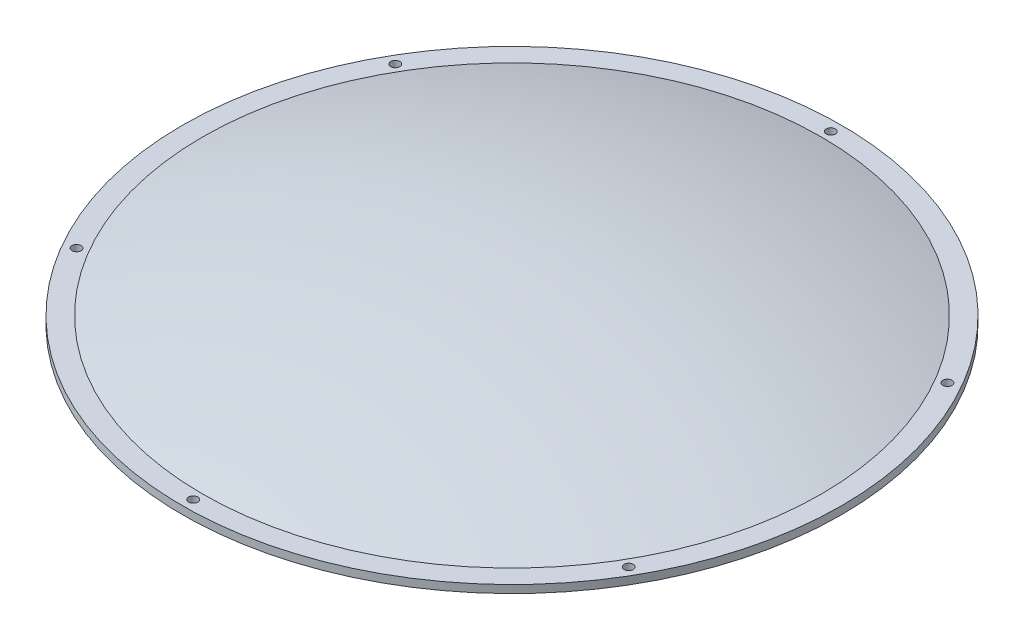
SolidWorks part; units mm, degrees
material "6061-T6 (SS)"
ref_plane "Front Plane" through (0, 0, 0) normal (0, 0, 1) x (1, 0, 0)
ref_plane "Top Plane" through (0, 0, 0) normal (0, 1, 0) x (1, 0, 0)
ref_plane "Right Plane" through (0, 0, 0) normal (1, 0, 0) x (0, 0, -1)
sketch "Sketch1" plane through (0, 0, 0) normal (0, 0, 1) x (1, 0, 0)
  line L0 (-107.3799, 282.8427) -> (107.3799, 282.8427)
  line L1 (0, 282.8427) -> (0, 102.1032)
  line L2 (0, 302.54) -> (0, 300)
  line L3 (100, 282.8427) -> (107, 282.8427)
  line L4 (0, 300) -> (-94.3927, 300) construction
  line L5 (100.4348, 285.3827) -> (107, 285.3827)
  line L6 (107, 282.8427) -> (107, 285.3827)
  line L7 (-100, 282.8427) -> (0, 0) construction
  line L8 (0, 0) -> (100, 282.8427) construction
  arc A0 (107.3799, 282.8427) -> (-107.3799, 282.8427) centre (0, 0) ccw
  arc A1 (100, 282.8427) -> (-100, 282.8427) centre (0, 0) ccw
  circle A2 centre (0, 0) radius 300 construction
  circle A3 centre (0, 0) radius 302.54 construction
  circle A4 centre (0, 0) radius 300 construction
  point P1 (149, 0)
  point P5 (0, 302.54)
  point P8 (143.4457, 43.8558)
  dimension "D1" = 300
  dimension "D2" = 200
  dimension "D4" = 2.54
  dimension "D5" = 107
  dimension "D3" = 2.54
revolve "Revolve1" add sketch "Sketch1" angle 360 about L1
sketch "Sketch4" plane through (0, 282.8427, 0) normal (0, -1, 0) x (1, 0, 0)
  circle A0 centre (0, 0) radius 103.5 construction
  circle A1 centre (0, 103.5) radius 1.4732
  circle A2 centre (89.6336, 51.75) radius 1.4732
  circle A3 centre (89.6336, -51.75) radius 1.4732
  circle A4 centre (0, -103.5) radius 1.4732
  circle A5 centre (-89.6336, -51.75) radius 1.4732
  circle A6 centre (-89.6336, 51.75) radius 1.4732
  dimension "D1" = 207
  dimension "D2" = 2.9464
  dimension "D3" = 6
extrude "Cut-Extrude1" cut sketch "Sketch4" against normal through all
ref_plane "Plane1" through (0, 152, 0) normal (0, 1, 0) x (-1, 0, 0)
sketch "Sketch5" plane through (0, 152, 0) normal (0, 1, 0) x (-1, 0, 0)
  line L0 (0.866, 0) -> (2.4628, 0) construction
  line L1 (0.433, -0.75) -> (0.866, 0)
  line L2 (0.866, 0) -> (0.433, 0.75)
  line L3 (0.433, 0.75) -> (-0.433, 0.75)
  line L4 (-0.433, 0.75) -> (-0.866, 0)
  line L5 (-0.866, 0) -> (-0.433, -0.75)
  line L6 (-0.433, -0.75) -> (0.433, -0.75)
  line L7 (2.557, -0.75) -> (3.423, -0.75)
  line L8 (2.363, 0.8643) -> (1.93, 1.6143)
  line L9 (1.93, 1.6143) -> (1.064, 1.6143)
  line L10 (1.064, 1.6143) -> (0.631, 0.8643)
  line L11 (0.631, 0.8643) -> (1.064, 0.1143)
  line L12 (1.064, 0.1143) -> (1.93, 0.1143)
  line L13 (1.93, 0.1143) -> (2.363, 0.8643)
  line L14 (2.124, 0) -> (2.557, -0.75)
  line L15 (2.557, 0.75) -> (2.124, 0)
  line L16 (3.423, 0.75) -> (2.557, 0.75)
  line L17 (3.856, 0) -> (3.423, 0.75)
  line L18 (3.423, -0.75) -> (3.856, 0)
  line L19 (3.621, 0.8643) -> (4.054, 0.1143)
  line L20 (4.054, 1.6143) -> (3.621, 0.8643)
  line L21 (4.92, 1.6143) -> (4.054, 1.6143)
  line L22 (5.353, 0.8643) -> (4.92, 1.6143)
  line L23 (4.92, 0.1143) -> (5.353, 0.8643)
  line L24 (4.054, 0.1143) -> (4.92, 0.1143)
  line L25 (5.547, -0.75) -> (6.413, -0.75)
  line L26 (5.114, 0) -> (5.547, -0.75)
  line L27 (5.547, 0.75) -> (5.114, 0)
  line L28 (6.413, 0.75) -> (5.547, 0.75)
  line L29 (6.846, 0) -> (6.413, 0.75)
  line L30 (6.413, -0.75) -> (6.846, 0)
  line L31 (6.611, 0.8643) -> (7.044, 0.1143)
  line L32 (7.044, 1.6143) -> (6.611, 0.8643)
  line L33 (7.91, 1.6143) -> (7.044, 1.6143)
  line L34 (8.343, 0.8643) -> (7.91, 1.6143)
  line L35 (7.91, 0.1143) -> (8.343, 0.8643)
  line L36 (7.044, 0.1143) -> (7.91, 0.1143)
  line L37 (8.537, -0.75) -> (9.403, -0.75)
  line L38 (8.104, 0) -> (8.537, -0.75)
  line L39 (8.537, 0.75) -> (8.104, 0)
  line L40 (9.403, 0.75) -> (8.537, 0.75)
  line L41 (9.836, 0) -> (9.403, 0.75)
  line L42 (9.403, -0.75) -> (9.836, 0)
  line L43 (9.601, 0.8643) -> (10.034, 0.1143)
  line L44 (10.034, 1.6143) -> (9.601, 0.8643)
  line L45 (10.9, 1.6143) -> (10.034, 1.6143)
  line L46 (11.333, 0.8643) -> (10.9, 1.6143)
  line L47 (10.9, 0.1143) -> (11.333, 0.8643)
  line L48 (10.034, 0.1143) -> (10.9, 0.1143)
  line L49 (11.527, -0.75) -> (12.393, -0.75)
  line L50 (11.094, 0) -> (11.527, -0.75)
  line L51 (11.527, 0.75) -> (11.094, 0)
  line L52 (12.393, 0.75) -> (11.527, 0.75)
  line L53 (12.826, 0) -> (12.393, 0.75)
  line L54 (12.393, -0.75) -> (12.826, 0)
  line L55 (12.591, 0.8643) -> (13.024, 0.1143)
  line L56 (13.024, 1.6143) -> (12.591, 0.8643)
  line L57 (13.89, 1.6143) -> (13.024, 1.6143)
  line L58 (14.323, 0.8643) -> (13.89, 1.6143)
  line L59 (13.89, 0.1143) -> (14.323, 0.8643)
  line L60 (13.024, 0.1143) -> (13.89, 0.1143)
  line L61 (14.517, -0.75) -> (15.383, -0.75)
  line L62 (14.084, 0) -> (14.517, -0.75)
  line L63 (14.517, 0.75) -> (14.084, 0)
  line L64 (15.383, 0.75) -> (14.517, 0.75)
  line L65 (15.816, 0) -> (15.383, 0.75)
  line L66 (15.383, -0.75) -> (15.816, 0)
  line L67 (15.581, 0.8643) -> (16.014, 0.1143)
  line L68 (16.014, 1.6143) -> (15.581, 0.8643)
  line L69 (16.88, 1.6143) -> (16.014, 1.6143)
  line L70 (17.313, 0.8643) -> (16.88, 1.6143)
  line L71 (16.88, 0.1143) -> (17.313, 0.8643)
  line L72 (16.014, 0.1143) -> (16.88, 0.1143)
  line L73 (17.507, -0.75) -> (18.373, -0.75)
  line L74 (17.074, 0) -> (17.507, -0.75)
  line L75 (17.507, 0.75) -> (17.074, 0)
  line L76 (18.373, 0.75) -> (17.507, 0.75)
  line L77 (18.806, 0) -> (18.373, 0.75)
  line L78 (18.373, -0.75) -> (18.806, 0)
  line L79 (18.571, 0.8643) -> (19.004, 0.1143)
  line L80 (19.004, 1.6143) -> (18.571, 0.8643)
  line L81 (19.87, 1.6143) -> (19.004, 1.6143)
  line L82 (20.303, 0.8643) -> (19.87, 1.6143)
  line L83 (19.87, 0.1143) -> (20.303, 0.8643)
  line L84 (19.004, 0.1143) -> (19.87, 0.1143)
  line L85 (20.497, -0.75) -> (21.363, -0.75)
  line L86 (20.064, 0) -> (20.497, -0.75)
  line L87 (20.497, 0.75) -> (20.064, 0)
  line L88 (21.363, 0.75) -> (20.497, 0.75)
  line L89 (21.796, 0) -> (21.363, 0.75)
  line L90 (21.363, -0.75) -> (21.796, 0)
  line L91 (21.561, 0.8643) -> (21.994, 0.1143)
  line L92 (21.994, 1.6143) -> (21.561, 0.8643)
  line L93 (22.86, 1.6143) -> (21.994, 1.6143)
  line L94 (23.293, 0.8643) -> (22.86, 1.6143)
  line L95 (22.86, 0.1143) -> (23.293, 0.8643)
  line L96 (21.994, 0.1143) -> (22.86, 0.1143)
  line L97 (23.487, -0.75) -> (24.353, -0.75)
  line L98 (23.054, 0) -> (23.487, -0.75)
  line L99 (23.487, 0.75) -> (23.054, 0)
  line L100 (24.353, 0.75) -> (23.487, 0.75)
  line L101 (24.786, 0) -> (24.353, 0.75)
  line L102 (24.353, -0.75) -> (24.786, 0)
  line L103 (24.551, 0.8643) -> (24.984, 0.1143)
  line L104 (24.984, 1.6143) -> (24.551, 0.8643)
  line L105 (25.85, 1.6143) -> (24.984, 1.6143)
  line L106 (26.283, 0.8643) -> (25.85, 1.6143)
  line L107 (25.85, 0.1143) -> (26.283, 0.8643)
  line L108 (24.984, 0.1143) -> (25.85, 0.1143)
  line L109 (26.477, -0.75) -> (27.343, -0.75)
  line L110 (26.044, 0) -> (26.477, -0.75)
  line L111 (26.477, 0.75) -> (26.044, 0)
  line L112 (27.343, 0.75) -> (26.477, 0.75)
  line L113 (27.776, 0) -> (27.343, 0.75)
  line L114 (27.343, -0.75) -> (27.776, 0)
  line L115 (27.541, 0.8643) -> (27.974, 0.1143)
  line L116 (27.974, 1.6143) -> (27.541, 0.8643)
  line L117 (28.84, 1.6143) -> (27.974, 1.6143)
  line L118 (29.273, 0.8643) -> (28.84, 1.6143)
  line L119 (28.84, 0.1143) -> (29.273, 0.8643)
  line L120 (27.974, 0.1143) -> (28.84, 0.1143)
  line L121 (-0.433, 0.98) -> (0.433, 0.98)
  line L122 (-0.866, 1.73) -> (-0.433, 0.98)
  line L123 (-0.433, 2.48) -> (-0.866, 1.73)
  line L124 (0.433, 2.48) -> (-0.433, 2.48)
  line L125 (0.866, 1.73) -> (0.433, 2.48)
  line L126 (0.433, 0.98) -> (0.866, 1.73)
  line L127 (0.631, 2.5943) -> (1.064, 1.8443)
  line L128 (1.064, 3.3443) -> (0.631, 2.5943)
  line L129 (1.93, 3.3443) -> (1.064, 3.3443)
  line L130 (2.363, 2.5943) -> (1.93, 3.3443)
  line L131 (1.93, 1.8443) -> (2.363, 2.5943)
  line L132 (1.064, 1.8443) -> (1.93, 1.8443)
  line L133 (2.557, 0.98) -> (3.423, 0.98)
  line L134 (2.124, 1.73) -> (2.557, 0.98)
  line L135 (2.557, 2.48) -> (2.124, 1.73)
  line L136 (3.423, 2.48) -> (2.557, 2.48)
  line L137 (3.856, 1.73) -> (3.423, 2.48)
  line L138 (3.423, 0.98) -> (3.856, 1.73)
  line L139 (3.621, 2.5943) -> (4.054, 1.8443)
  line L140 (4.054, 3.3443) -> (3.621, 2.5943)
  line L141 (4.92, 3.3443) -> (4.054, 3.3443)
  line L142 (5.353, 2.5943) -> (4.92, 3.3443)
  line L143 (4.92, 1.8443) -> (5.353, 2.5943)
  line L144 (4.054, 1.8443) -> (4.92, 1.8443)
  line L145 (5.547, 0.98) -> (6.413, 0.98)
  line L146 (5.114, 1.73) -> (5.547, 0.98)
  line L147 (5.547, 2.48) -> (5.114, 1.73)
  line L148 (6.413, 2.48) -> (5.547, 2.48)
  line L149 (6.846, 1.73) -> (6.413, 2.48)
  line L150 (6.413, 0.98) -> (6.846, 1.73)
  line L151 (6.611, 2.5943) -> (7.044, 1.8443)
  line L152 (7.044, 3.3443) -> (6.611, 2.5943)
  line L153 (7.91, 3.3443) -> (7.044, 3.3443)
  line L154 (8.343, 2.5943) -> (7.91, 3.3443)
  line L155 (7.91, 1.8443) -> (8.343, 2.5943)
  line L156 (7.044, 1.8443) -> (7.91, 1.8443)
  line L157 (8.537, 0.98) -> (9.403, 0.98)
  line L158 (8.104, 1.73) -> (8.537, 0.98)
  line L159 (8.537, 2.48) -> (8.104, 1.73)
  line L160 (9.403, 2.48) -> (8.537, 2.48)
  line L161 (9.836, 1.73) -> (9.403, 2.48)
  line L162 (9.403, 0.98) -> (9.836, 1.73)
  line L163 (9.601, 2.5943) -> (10.034, 1.8443)
  line L164 (10.034, 3.3443) -> (9.601, 2.5943)
  line L165 (10.9, 3.3443) -> (10.034, 3.3443)
  line L166 (11.333, 2.5943) -> (10.9, 3.3443)
  line L167 (10.9, 1.8443) -> (11.333, 2.5943)
  line L168 (10.034, 1.8443) -> (10.9, 1.8443)
  line L169 (11.527, 0.98) -> (12.393, 0.98)
  line L170 (11.094, 1.73) -> (11.527, 0.98)
  line L171 (11.527, 2.48) -> (11.094, 1.73)
  line L172 (12.393, 2.48) -> (11.527, 2.48)
  line L173 (12.826, 1.73) -> (12.393, 2.48)
  line L174 (12.393, 0.98) -> (12.826, 1.73)
  line L175 (12.591, 2.5943) -> (13.024, 1.8443)
  line L176 (13.024, 3.3443) -> (12.591, 2.5943)
  line L177 (13.89, 3.3443) -> (13.024, 3.3443)
  line L178 (14.323, 2.5943) -> (13.89, 3.3443)
  line L179 (13.89, 1.8443) -> (14.323, 2.5943)
  line L180 (13.024, 1.8443) -> (13.89, 1.8443)
  line L181 (14.517, 0.98) -> (15.383, 0.98)
  line L182 (14.084, 1.73) -> (14.517, 0.98)
  line L183 (14.517, 2.48) -> (14.084, 1.73)
  line L184 (15.383, 2.48) -> (14.517, 2.48)
  line L185 (15.816, 1.73) -> (15.383, 2.48)
  line L186 (15.383, 0.98) -> (15.816, 1.73)
  line L187 (15.581, 2.5943) -> (16.014, 1.8443)
  line L188 (16.014, 3.3443) -> (15.581, 2.5943)
  line L189 (16.88, 3.3443) -> (16.014, 3.3443)
  line L190 (17.313, 2.5943) -> (16.88, 3.3443)
  line L191 (16.88, 1.8443) -> (17.313, 2.5943)
  line L192 (16.014, 1.8443) -> (16.88, 1.8443)
  line L193 (17.507, 0.98) -> (18.373, 0.98)
  line L194 (17.074, 1.73) -> (17.507, 0.98)
  line L195 (17.507, 2.48) -> (17.074, 1.73)
  line L196 (18.373, 2.48) -> (17.507, 2.48)
  line L197 (18.806, 1.73) -> (18.373, 2.48)
  line L198 (18.373, 0.98) -> (18.806, 1.73)
  line L199 (18.571, 2.5943) -> (19.004, 1.8443)
  line L200 (19.004, 3.3443) -> (18.571, 2.5943)
  line L201 (19.87, 3.3443) -> (19.004, 3.3443)
  line L202 (20.303, 2.5943) -> (19.87, 3.3443)
  line L203 (19.87, 1.8443) -> (20.303, 2.5943)
  line L204 (19.004, 1.8443) -> (19.87, 1.8443)
  line L205 (20.497, 0.98) -> (21.363, 0.98)
  line L206 (20.064, 1.73) -> (20.497, 0.98)
  line L207 (20.497, 2.48) -> (20.064, 1.73)
  line L208 (21.363, 2.48) -> (20.497, 2.48)
  line L209 (21.796, 1.73) -> (21.363, 2.48)
  line L210 (21.363, 0.98) -> (21.796, 1.73)
  line L211 (21.561, 2.5943) -> (21.994, 1.8443)
  line L212 (21.994, 3.3443) -> (21.561, 2.5943)
  line L213 (22.86, 3.3443) -> (21.994, 3.3443)
  line L214 (23.293, 2.5943) -> (22.86, 3.3443)
  line L215 (22.86, 1.8443) -> (23.293, 2.5943)
  line L216 (21.994, 1.8443) -> (22.86, 1.8443)
  line L217 (23.487, 0.98) -> (24.353, 0.98)
  line L218 (23.054, 1.73) -> (23.487, 0.98)
  line L219 (23.487, 2.48) -> (23.054, 1.73)
  line L220 (24.353, 2.48) -> (23.487, 2.48)
  line L221 (24.786, 1.73) -> (24.353, 2.48)
  line L222 (24.353, 0.98) -> (24.786, 1.73)
  line L223 (24.551, 2.5943) -> (24.984, 1.8443)
  line L224 (24.984, 3.3443) -> (24.551, 2.5943)
  line L225 (25.85, 3.3443) -> (24.984, 3.3443)
  line L226 (26.283, 2.5943) -> (25.85, 3.3443)
  line L227 (25.85, 1.8443) -> (26.283, 2.5943)
  line L228 (24.984, 1.8443) -> (25.85, 1.8443)
  line L229 (26.477, 0.98) -> (27.343, 0.98)
  line L230 (26.044, 1.73) -> (26.477, 0.98)
  line L231 (26.477, 2.48) -> (26.044, 1.73)
  line L232 (27.343, 2.48) -> (26.477, 2.48)
  line L233 (27.776, 1.73) -> (27.343, 2.48)
  line L234 (27.343, 0.98) -> (27.776, 1.73)
  line L235 (27.541, 2.5943) -> (27.974, 1.8443)
  line L236 (27.974, 3.3443) -> (27.541, 2.5943)
  line L237 (28.84, 3.3443) -> (27.974, 3.3443)
  line L238 (29.273, 2.5943) -> (28.84, 3.3443)
  line L239 (28.84, 1.8443) -> (29.273, 2.5943)
  line L240 (27.974, 1.8443) -> (28.84, 1.8443)
  line L241 (-0.433, 2.71) -> (0.433, 2.71)
  line L242 (-0.866, 3.46) -> (-0.433, 2.71)
  line L243 (-0.433, 4.21) -> (-0.866, 3.46)
  line L244 (0.433, 4.21) -> (-0.433, 4.21)
  line L245 (0.866, 3.46) -> (0.433, 4.21)
  line L246 (0.433, 2.71) -> (0.866, 3.46)
  line L247 (0.631, 4.3243) -> (1.064, 3.5743)
  line L248 (1.064, 5.0743) -> (0.631, 4.3243)
  line L249 (1.93, 5.0743) -> (1.064, 5.0743)
  line L250 (2.363, 4.3243) -> (1.93, 5.0743)
  line L251 (1.93, 3.5743) -> (2.363, 4.3243)
  line L252 (1.064, 3.5743) -> (1.93, 3.5743)
  line L253 (2.557, 2.71) -> (3.423, 2.71)
  line L254 (2.124, 3.46) -> (2.557, 2.71)
  line L255 (2.557, 4.21) -> (2.124, 3.46)
  line L256 (3.423, 4.21) -> (2.557, 4.21)
  line L257 (3.856, 3.46) -> (3.423, 4.21)
  line L258 (3.423, 2.71) -> (3.856, 3.46)
  line L259 (3.621, 4.3243) -> (4.054, 3.5743)
  line L260 (4.054, 5.0743) -> (3.621, 4.3243)
  line L261 (4.92, 5.0743) -> (4.054, 5.0743)
  line L262 (5.353, 4.3243) -> (4.92, 5.0743)
  line L263 (4.92, 3.5743) -> (5.353, 4.3243)
  line L264 (4.054, 3.5743) -> (4.92, 3.5743)
  line L265 (5.547, 2.71) -> (6.413, 2.71)
  line L266 (5.114, 3.46) -> (5.547, 2.71)
  line L267 (5.547, 4.21) -> (5.114, 3.46)
  line L268 (6.413, 4.21) -> (5.547, 4.21)
  line L269 (6.846, 3.46) -> (6.413, 4.21)
  line L270 (6.413, 2.71) -> (6.846, 3.46)
  line L271 (6.611, 4.3243) -> (7.044, 3.5743)
  line L272 (7.044, 5.0743) -> (6.611, 4.3243)
  line L273 (7.91, 5.0743) -> (7.044, 5.0743)
  line L274 (8.343, 4.3243) -> (7.91, 5.0743)
  line L275 (7.91, 3.5743) -> (8.343, 4.3243)
  line L276 (7.044, 3.5743) -> (7.91, 3.5743)
  line L277 (8.537, 2.71) -> (9.403, 2.71)
  line L278 (8.104, 3.46) -> (8.537, 2.71)
  line L279 (8.537, 4.21) -> (8.104, 3.46)
  line L280 (9.403, 4.21) -> (8.537, 4.21)
  line L281 (9.836, 3.46) -> (9.403, 4.21)
  line L282 (9.403, 2.71) -> (9.836, 3.46)
  line L283 (9.601, 4.3243) -> (10.034, 3.5743)
  line L284 (10.034, 5.0743) -> (9.601, 4.3243)
  line L285 (10.9, 5.0743) -> (10.034, 5.0743)
  line L286 (11.333, 4.3243) -> (10.9, 5.0743)
  line L287 (10.9, 3.5743) -> (11.333, 4.3243)
  line L288 (10.034, 3.5743) -> (10.9, 3.5743)
  line L289 (11.527, 2.71) -> (12.393, 2.71)
  line L290 (11.094, 3.46) -> (11.527, 2.71)
  line L291 (11.527, 4.21) -> (11.094, 3.46)
  line L292 (12.393, 4.21) -> (11.527, 4.21)
  line L293 (12.826, 3.46) -> (12.393, 4.21)
  line L294 (12.393, 2.71) -> (12.826, 3.46)
  line L295 (12.591, 4.3243) -> (13.024, 3.5743)
  line L296 (13.024, 5.0743) -> (12.591, 4.3243)
  line L297 (13.89, 5.0743) -> (13.024, 5.0743)
  line L298 (14.323, 4.3243) -> (13.89, 5.0743)
  line L299 (13.89, 3.5743) -> (14.323, 4.3243)
  line L300 (13.024, 3.5743) -> (13.89, 3.5743)
  line L301 (14.517, 2.71) -> (15.383, 2.71)
  line L302 (14.084, 3.46) -> (14.517, 2.71)
  line L303 (14.517, 4.21) -> (14.084, 3.46)
  line L304 (15.383, 4.21) -> (14.517, 4.21)
  line L305 (15.816, 3.46) -> (15.383, 4.21)
  line L306 (15.383, 2.71) -> (15.816, 3.46)
  line L307 (15.581, 4.3243) -> (16.014, 3.5743)
  line L308 (16.014, 5.0743) -> (15.581, 4.3243)
  line L309 (16.88, 5.0743) -> (16.014, 5.0743)
  line L310 (17.313, 4.3243) -> (16.88, 5.0743)
  line L311 (16.88, 3.5743) -> (17.313, 4.3243)
  line L312 (16.014, 3.5743) -> (16.88, 3.5743)
  line L313 (17.507, 2.71) -> (18.373, 2.71)
  line L314 (17.074, 3.46) -> (17.507, 2.71)
  line L315 (17.507, 4.21) -> (17.074, 3.46)
  line L316 (18.373, 4.21) -> (17.507, 4.21)
  line L317 (18.806, 3.46) -> (18.373, 4.21)
  line L318 (18.373, 2.71) -> (18.806, 3.46)
  line L319 (18.571, 4.3243) -> (19.004, 3.5743)
  line L320 (19.004, 5.0743) -> (18.571, 4.3243)
  line L321 (19.87, 5.0743) -> (19.004, 5.0743)
  line L322 (20.303, 4.3243) -> (19.87, 5.0743)
  line L323 (19.87, 3.5743) -> (20.303, 4.3243)
  line L324 (19.004, 3.5743) -> (19.87, 3.5743)
  line L325 (20.497, 2.71) -> (21.363, 2.71)
  line L326 (20.064, 3.46) -> (20.497, 2.71)
  line L327 (20.497, 4.21) -> (20.064, 3.46)
  line L328 (21.363, 4.21) -> (20.497, 4.21)
  line L329 (21.796, 3.46) -> (21.363, 4.21)
  line L330 (21.363, 2.71) -> (21.796, 3.46)
  line L331 (21.561, 4.3243) -> (21.994, 3.5743)
  line L332 (21.994, 5.0743) -> (21.561, 4.3243)
  line L333 (22.86, 5.0743) -> (21.994, 5.0743)
  line L334 (23.293, 4.3243) -> (22.86, 5.0743)
  line L335 (22.86, 3.5743) -> (23.293, 4.3243)
  line L336 (21.994, 3.5743) -> (22.86, 3.5743)
  line L337 (23.487, 2.71) -> (24.353, 2.71)
  line L338 (23.054, 3.46) -> (23.487, 2.71)
  line L339 (23.487, 4.21) -> (23.054, 3.46)
  line L340 (24.353, 4.21) -> (23.487, 4.21)
  line L341 (24.786, 3.46) -> (24.353, 4.21)
  line L342 (24.353, 2.71) -> (24.786, 3.46)
  line L343 (24.551, 4.3243) -> (24.984, 3.5743)
  line L344 (24.984, 5.0743) -> (24.551, 4.3243)
  line L345 (25.85, 5.0743) -> (24.984, 5.0743)
  line L346 (26.283, 4.3243) -> (25.85, 5.0743)
  line L347 (25.85, 3.5743) -> (26.283, 4.3243)
  line L348 (24.984, 3.5743) -> (25.85, 3.5743)
  line L349 (26.477, 2.71) -> (27.343, 2.71)
  line L350 (26.044, 3.46) -> (26.477, 2.71)
  line L351 (26.477, 4.21) -> (26.044, 3.46)
  line L352 (27.343, 4.21) -> (26.477, 4.21)
  line L353 (27.776, 3.46) -> (27.343, 4.21)
  line L354 (27.343, 2.71) -> (27.776, 3.46)
  line L355 (27.541, 4.3243) -> (27.974, 3.5743)
  line L356 (27.974, 5.0743) -> (27.541, 4.3243)
  line L357 (28.84, 5.0743) -> (27.974, 5.0743)
  line L358 (29.273, 4.3243) -> (28.84, 5.0743)
  line L359 (28.84, 3.5743) -> (29.273, 4.3243)
  line L360 (27.974, 3.5743) -> (28.84, 3.5743)
  line L361 (-0.433, 4.44) -> (0.433, 4.44)
  line L362 (-0.866, 5.19) -> (-0.433, 4.44)
  line L363 (-0.433, 5.94) -> (-0.866, 5.19)
  line L364 (0.433, 5.94) -> (-0.433, 5.94)
  line L365 (0.866, 5.19) -> (0.433, 5.94)
  line L366 (0.433, 4.44) -> (0.866, 5.19)
  line L367 (0.631, 6.0543) -> (1.064, 5.3043)
  line L368 (1.064, 6.8043) -> (0.631, 6.0543)
  line L369 (1.93, 6.8043) -> (1.064, 6.8043)
  line L370 (2.363, 6.0543) -> (1.93, 6.8043)
  line L371 (1.93, 5.3043) -> (2.363, 6.0543)
  line L372 (1.064, 5.3043) -> (1.93, 5.3043)
  line L373 (2.557, 4.44) -> (3.423, 4.44)
  line L374 (2.124, 5.19) -> (2.557, 4.44)
  line L375 (2.557, 5.94) -> (2.124, 5.19)
  line L376 (3.423, 5.94) -> (2.557, 5.94)
  line L377 (3.856, 5.19) -> (3.423, 5.94)
  line L378 (3.423, 4.44) -> (3.856, 5.19)
  line L379 (3.621, 6.0543) -> (4.054, 5.3043)
  line L380 (4.054, 6.8043) -> (3.621, 6.0543)
  line L381 (4.92, 6.8043) -> (4.054, 6.8043)
  line L382 (5.353, 6.0543) -> (4.92, 6.8043)
  line L383 (4.92, 5.3043) -> (5.353, 6.0543)
  line L384 (4.054, 5.3043) -> (4.92, 5.3043)
  line L385 (5.547, 4.44) -> (6.413, 4.44)
  line L386 (5.114, 5.19) -> (5.547, 4.44)
  line L387 (5.547, 5.94) -> (5.114, 5.19)
  line L388 (6.413, 5.94) -> (5.547, 5.94)
  line L389 (6.846, 5.19) -> (6.413, 5.94)
  line L390 (6.413, 4.44) -> (6.846, 5.19)
  line L391 (6.611, 6.0543) -> (7.044, 5.3043)
  line L392 (7.044, 6.8043) -> (6.611, 6.0543)
  line L393 (7.91, 6.8043) -> (7.044, 6.8043)
  line L394 (8.343, 6.0543) -> (7.91, 6.8043)
  line L395 (7.91, 5.3043) -> (8.343, 6.0543)
  line L396 (7.044, 5.3043) -> (7.91, 5.3043)
  line L397 (8.537, 4.44) -> (9.403, 4.44)
  line L398 (8.104, 5.19) -> (8.537, 4.44)
  line L399 (8.537, 5.94) -> (8.104, 5.19)
  line L400 (9.403, 5.94) -> (8.537, 5.94)
  line L401 (9.836, 5.19) -> (9.403, 5.94)
  line L402 (9.403, 4.44) -> (9.836, 5.19)
  line L403 (9.601, 6.0543) -> (10.034, 5.3043)
  line L404 (10.034, 6.8043) -> (9.601, 6.0543)
  line L405 (10.9, 6.8043) -> (10.034, 6.8043)
  line L406 (11.333, 6.0543) -> (10.9, 6.8043)
  line L407 (10.9, 5.3043) -> (11.333, 6.0543)
  line L408 (10.034, 5.3043) -> (10.9, 5.3043)
  line L409 (11.527, 4.44) -> (12.393, 4.44)
  line L410 (11.094, 5.19) -> (11.527, 4.44)
  line L411 (11.527, 5.94) -> (11.094, 5.19)
  line L412 (12.393, 5.94) -> (11.527, 5.94)
  line L413 (12.826, 5.19) -> (12.393, 5.94)
  line L414 (12.393, 4.44) -> (12.826, 5.19)
  line L415 (12.591, 6.0543) -> (13.024, 5.3043)
  line L416 (13.024, 6.8043) -> (12.591, 6.0543)
  line L417 (13.89, 6.8043) -> (13.024, 6.8043)
  line L418 (14.323, 6.0543) -> (13.89, 6.8043)
  line L419 (13.89, 5.3043) -> (14.323, 6.0543)
  line L420 (13.024, 5.3043) -> (13.89, 5.3043)
  line L421 (14.517, 4.44) -> (15.383, 4.44)
  line L422 (14.084, 5.19) -> (14.517, 4.44)
  line L423 (14.517, 5.94) -> (14.084, 5.19)
  line L424 (15.383, 5.94) -> (14.517, 5.94)
  line L425 (15.816, 5.19) -> (15.383, 5.94)
  line L426 (15.383, 4.44) -> (15.816, 5.19)
  line L427 (15.581, 6.0543) -> (16.014, 5.3043)
  line L428 (16.014, 6.8043) -> (15.581, 6.0543)
  line L429 (16.88, 6.8043) -> (16.014, 6.8043)
  line L430 (17.313, 6.0543) -> (16.88, 6.8043)
  line L431 (16.88, 5.3043) -> (17.313, 6.0543)
  line L432 (16.014, 5.3043) -> (16.88, 5.3043)
  line L433 (17.507, 4.44) -> (18.373, 4.44)
  line L434 (17.074, 5.19) -> (17.507, 4.44)
  line L435 (17.507, 5.94) -> (17.074, 5.19)
  line L436 (18.373, 5.94) -> (17.507, 5.94)
  line L437 (18.806, 5.19) -> (18.373, 5.94)
  line L438 (18.373, 4.44) -> (18.806, 5.19)
  line L439 (18.571, 6.0543) -> (19.004, 5.3043)
  line L440 (19.004, 6.8043) -> (18.571, 6.0543)
  line L441 (19.87, 6.8043) -> (19.004, 6.8043)
  line L442 (20.303, 6.0543) -> (19.87, 6.8043)
  line L443 (19.87, 5.3043) -> (20.303, 6.0543)
  line L444 (19.004, 5.3043) -> (19.87, 5.3043)
  line L445 (20.497, 4.44) -> (21.363, 4.44)
  line L446 (20.064, 5.19) -> (20.497, 4.44)
  line L447 (20.497, 5.94) -> (20.064, 5.19)
  line L448 (21.363, 5.94) -> (20.497, 5.94)
  line L449 (21.796, 5.19) -> (21.363, 5.94)
  line L450 (21.363, 4.44) -> (21.796, 5.19)
  line L451 (21.561, 6.0543) -> (21.994, 5.3043)
  line L452 (21.994, 6.8043) -> (21.561, 6.0543)
  line L453 (22.86, 6.8043) -> (21.994, 6.8043)
  line L454 (23.293, 6.0543) -> (22.86, 6.8043)
  line L455 (22.86, 5.3043) -> (23.293, 6.0543)
  line L456 (21.994, 5.3043) -> (22.86, 5.3043)
  line L457 (23.487, 4.44) -> (24.353, 4.44)
  line L458 (23.054, 5.19) -> (23.487, 4.44)
  line L459 (23.487, 5.94) -> (23.054, 5.19)
  line L460 (24.353, 5.94) -> (23.487, 5.94)
  line L461 (24.786, 5.19) -> (24.353, 5.94)
  line L462 (24.353, 4.44) -> (24.786, 5.19)
  line L463 (24.551, 6.0543) -> (24.984, 5.3043)
  line L464 (24.984, 6.8043) -> (24.551, 6.0543)
  line L465 (25.85, 6.8043) -> (24.984, 6.8043)
  line L466 (26.283, 6.0543) -> (25.85, 6.8043)
  line L467 (25.85, 5.3043) -> (26.283, 6.0543)
  line L468 (24.984, 5.3043) -> (25.85, 5.3043)
  line L469 (26.477, 4.44) -> (27.343, 4.44)
  line L470 (26.044, 5.19) -> (26.477, 4.44)
  line L471 (26.477, 5.94) -> (26.044, 5.19)
  line L472 (27.343, 5.94) -> (26.477, 5.94)
  line L473 (27.776, 5.19) -> (27.343, 5.94)
  line L474 (27.343, 4.44) -> (27.776, 5.19)
  line L475 (27.541, 6.0543) -> (27.974, 5.3043)
  line L476 (27.974, 6.8043) -> (27.541, 6.0543)
  line L477 (28.84, 6.8043) -> (27.974, 6.8043)
  line L478 (29.273, 6.0543) -> (28.84, 6.8043)
  line L479 (28.84, 5.3043) -> (29.273, 6.0543)
  line L480 (27.974, 5.3043) -> (28.84, 5.3043)
  line L481 (-0.433, 6.17) -> (0.433, 6.17)
  line L482 (-0.866, 6.92) -> (-0.433, 6.17)
  line L483 (-0.433, 7.67) -> (-0.866, 6.92)
  line L484 (0.433, 7.67) -> (-0.433, 7.67)
  line L485 (0.866, 6.92) -> (0.433, 7.67)
  line L486 (0.433, 6.17) -> (0.866, 6.92)
  line L487 (0.631, 7.7843) -> (1.064, 7.0343)
  line L488 (1.064, 8.5343) -> (0.631, 7.7843)
  line L489 (1.93, 8.5343) -> (1.064, 8.5343)
  line L490 (2.363, 7.7843) -> (1.93, 8.5343)
  line L491 (1.93, 7.0343) -> (2.363, 7.7843)
  line L492 (1.064, 7.0343) -> (1.93, 7.0343)
  line L493 (2.557, 6.17) -> (3.423, 6.17)
  line L494 (2.124, 6.92) -> (2.557, 6.17)
  line L495 (2.557, 7.67) -> (2.124, 6.92)
  line L496 (3.423, 7.67) -> (2.557, 7.67)
  line L497 (3.856, 6.92) -> (3.423, 7.67)
  line L498 (3.423, 6.17) -> (3.856, 6.92)
  line L499 (3.621, 7.7843) -> (4.054, 7.0343)
  line L500 (4.054, 8.5343) -> (3.621, 7.7843)
  line L501 (4.92, 8.5343) -> (4.054, 8.5343)
  line L502 (5.353, 7.7843) -> (4.92, 8.5343)
  line L503 (4.92, 7.0343) -> (5.353, 7.7843)
  line L504 (4.054, 7.0343) -> (4.92, 7.0343)
  line L505 (5.547, 6.17) -> (6.413, 6.17)
  line L506 (5.114, 6.92) -> (5.547, 6.17)
  line L507 (5.547, 7.67) -> (5.114, 6.92)
  line L508 (6.413, 7.67) -> (5.547, 7.67)
  line L509 (6.846, 6.92) -> (6.413, 7.67)
  line L510 (6.413, 6.17) -> (6.846, 6.92)
  line L511 (6.611, 7.7843) -> (7.044, 7.0343)
  line L512 (7.044, 8.5343) -> (6.611, 7.7843)
  line L513 (7.91, 8.5343) -> (7.044, 8.5343)
  line L514 (8.343, 7.7843) -> (7.91, 8.5343)
  line L515 (7.91, 7.0343) -> (8.343, 7.7843)
  line L516 (7.044, 7.0343) -> (7.91, 7.0343)
  line L517 (8.537, 6.17) -> (9.403, 6.17)
  line L518 (8.104, 6.92) -> (8.537, 6.17)
  line L519 (8.537, 7.67) -> (8.104, 6.92)
  line L520 (9.403, 7.67) -> (8.537, 7.67)
  line L521 (9.836, 6.92) -> (9.403, 7.67)
  line L522 (9.403, 6.17) -> (9.836, 6.92)
  line L523 (9.601, 7.7843) -> (10.034, 7.0343)
  line L524 (10.034, 8.5343) -> (9.601, 7.7843)
  line L525 (10.9, 8.5343) -> (10.034, 8.5343)
  line L526 (11.333, 7.7843) -> (10.9, 8.5343)
  line L527 (10.9, 7.0343) -> (11.333, 7.7843)
  line L528 (10.034, 7.0343) -> (10.9, 7.0343)
  line L529 (11.527, 6.17) -> (12.393, 6.17)
  line L530 (11.094, 6.92) -> (11.527, 6.17)
  line L531 (11.527, 7.67) -> (11.094, 6.92)
  line L532 (12.393, 7.67) -> (11.527, 7.67)
  line L533 (12.826, 6.92) -> (12.393, 7.67)
  line L534 (12.393, 6.17) -> (12.826, 6.92)
  line L535 (12.591, 7.7843) -> (13.024, 7.0343)
  line L536 (13.024, 8.5343) -> (12.591, 7.7843)
  line L537 (13.89, 8.5343) -> (13.024, 8.5343)
  line L538 (14.323, 7.7843) -> (13.89, 8.5343)
  line L539 (13.89, 7.0343) -> (14.323, 7.7843)
  line L540 (13.024, 7.0343) -> (13.89, 7.0343)
  line L541 (14.517, 6.17) -> (15.383, 6.17)
  line L542 (14.084, 6.92) -> (14.517, 6.17)
  line L543 (14.517, 7.67) -> (14.084, 6.92)
  line L544 (15.383, 7.67) -> (14.517, 7.67)
  line L545 (15.816, 6.92) -> (15.383, 7.67)
  line L546 (15.383, 6.17) -> (15.816, 6.92)
  line L547 (15.581, 7.7843) -> (16.014, 7.0343)
  line L548 (16.014, 8.5343) -> (15.581, 7.7843)
  line L549 (16.88, 8.5343) -> (16.014, 8.5343)
  line L550 (17.313, 7.7843) -> (16.88, 8.5343)
  line L551 (16.88, 7.0343) -> (17.313, 7.7843)
  line L552 (16.014, 7.0343) -> (16.88, 7.0343)
  line L553 (17.507, 6.17) -> (18.373, 6.17)
  line L554 (17.074, 6.92) -> (17.507, 6.17)
  line L555 (17.507, 7.67) -> (17.074, 6.92)
  line L556 (18.373, 7.67) -> (17.507, 7.67)
  line L557 (18.806, 6.92) -> (18.373, 7.67)
  line L558 (18.373, 6.17) -> (18.806, 6.92)
  line L559 (18.571, 7.7843) -> (19.004, 7.0343)
  line L560 (19.004, 8.5343) -> (18.571, 7.7843)
  line L561 (19.87, 8.5343) -> (19.004, 8.5343)
  line L562 (20.303, 7.7843) -> (19.87, 8.5343)
  line L563 (19.87, 7.0343) -> (20.303, 7.7843)
  line L564 (19.004, 7.0343) -> (19.87, 7.0343)
  line L565 (20.497, 6.17) -> (21.363, 6.17)
  line L566 (20.064, 6.92) -> (20.497, 6.17)
  line L567 (20.497, 7.67) -> (20.064, 6.92)
  line L568 (21.363, 7.67) -> (20.497, 7.67)
  line L569 (21.796, 6.92) -> (21.363, 7.67)
  line L570 (21.363, 6.17) -> (21.796, 6.92)
  line L571 (21.561, 7.7843) -> (21.994, 7.0343)
  line L572 (21.994, 8.5343) -> (21.561, 7.7843)
  line L573 (22.86, 8.5343) -> (21.994, 8.5343)
  line L574 (23.293, 7.7843) -> (22.86, 8.5343)
  line L575 (22.86, 7.0343) -> (23.293, 7.7843)
  line L576 (21.994, 7.0343) -> (22.86, 7.0343)
  line L577 (23.487, 6.17) -> (24.353, 6.17)
  line L578 (23.054, 6.92) -> (23.487, 6.17)
  line L579 (23.487, 7.67) -> (23.054, 6.92)
  line L580 (24.353, 7.67) -> (23.487, 7.67)
  line L581 (24.786, 6.92) -> (24.353, 7.67)
  line L582 (24.353, 6.17) -> (24.786, 6.92)
  line L583 (24.551, 7.7843) -> (24.984, 7.0343)
  line L584 (24.984, 8.5343) -> (24.551, 7.7843)
  line L585 (25.85, 8.5343) -> (24.984, 8.5343)
  line L586 (26.283, 7.7843) -> (25.85, 8.5343)
  line L587 (25.85, 7.0343) -> (26.283, 7.7843)
  line L588 (24.984, 7.0343) -> (25.85, 7.0343)
  line L589 (26.477, 6.17) -> (27.343, 6.17)
  line L590 (26.044, 6.92) -> (26.477, 6.17)
  line L591 (26.477, 7.67) -> (26.044, 6.92)
  line L592 (27.343, 7.67) -> (26.477, 7.67)
  line L593 (27.776, 6.92) -> (27.343, 7.67)
  line L594 (27.343, 6.17) -> (27.776, 6.92)
  line L595 (27.541, 7.7843) -> (27.974, 7.0343)
  line L596 (27.974, 8.5343) -> (27.541, 7.7843)
  line L597 (28.84, 8.5343) -> (27.974, 8.5343)
  line L598 (29.273, 7.7843) -> (28.84, 8.5343)
  line L599 (28.84, 7.0343) -> (29.273, 7.7843)
  line L600 (27.974, 7.0343) -> (28.84, 7.0343)
  line L601 (-0.433, 7.9) -> (0.433, 7.9)
  line L602 (-0.866, 8.65) -> (-0.433, 7.9)
  line L603 (-0.433, 9.4) -> (-0.866, 8.65)
  line L604 (0.433, 9.4) -> (-0.433, 9.4)
  line L605 (0.866, 8.65) -> (0.433, 9.4)
  line L606 (0.433, 7.9) -> (0.866, 8.65)
  line L607 (0.631, 9.5143) -> (1.064, 8.7643)
  line L608 (1.064, 10.2643) -> (0.631, 9.5143)
  line L609 (1.93, 10.2643) -> (1.064, 10.2643)
  line L610 (2.363, 9.5143) -> (1.93, 10.2643)
  line L611 (1.93, 8.7643) -> (2.363, 9.5143)
  line L612 (1.064, 8.7643) -> (1.93, 8.7643)
  line L613 (2.557, 7.9) -> (3.423, 7.9)
  line L614 (2.124, 8.65) -> (2.557, 7.9)
  line L615 (2.557, 9.4) -> (2.124, 8.65)
  line L616 (3.423, 9.4) -> (2.557, 9.4)
  line L617 (3.856, 8.65) -> (3.423, 9.4)
  line L618 (3.423, 7.9) -> (3.856, 8.65)
  line L619 (3.621, 9.5143) -> (4.054, 8.7643)
  line L620 (4.054, 10.2643) -> (3.621, 9.5143)
  line L621 (4.92, 10.2643) -> (4.054, 10.2643)
  line L622 (5.353, 9.5143) -> (4.92, 10.2643)
  line L623 (4.92, 8.7643) -> (5.353, 9.5143)
  line L624 (4.054, 8.7643) -> (4.92, 8.7643)
  line L625 (5.547, 7.9) -> (6.413, 7.9)
  line L626 (5.114, 8.65) -> (5.547, 7.9)
  line L627 (5.547, 9.4) -> (5.114, 8.65)
  line L628 (6.413, 9.4) -> (5.547, 9.4)
  line L629 (6.846, 8.65) -> (6.413, 9.4)
  line L630 (6.413, 7.9) -> (6.846, 8.65)
  line L631 (6.611, 9.5143) -> (7.044, 8.7643)
  line L632 (7.044, 10.2643) -> (6.611, 9.5143)
  line L633 (7.91, 10.2643) -> (7.044, 10.2643)
  line L634 (8.343, 9.5143) -> (7.91, 10.2643)
  line L635 (7.91, 8.7643) -> (8.343, 9.5143)
  line L636 (7.044, 8.7643) -> (7.91, 8.7643)
  line L637 (8.537, 7.9) -> (9.403, 7.9)
  line L638 (8.104, 8.65) -> (8.537, 7.9)
  line L639 (8.537, 9.4) -> (8.104, 8.65)
  line L640 (9.403, 9.4) -> (8.537, 9.4)
  line L641 (9.836, 8.65) -> (9.403, 9.4)
  line L642 (9.403, 7.9) -> (9.836, 8.65)
  line L643 (9.601, 9.5143) -> (10.034, 8.7643)
  line L644 (10.034, 10.2643) -> (9.601, 9.5143)
  line L645 (10.9, 10.2643) -> (10.034, 10.2643)
  line L646 (11.333, 9.5143) -> (10.9, 10.2643)
  line L647 (10.9, 8.7643) -> (11.333, 9.5143)
  line L648 (10.034, 8.7643) -> (10.9, 8.7643)
  line L649 (11.527, 7.9) -> (12.393, 7.9)
  line L650 (11.094, 8.65) -> (11.527, 7.9)
  line L651 (11.527, 9.4) -> (11.094, 8.65)
  line L652 (12.393, 9.4) -> (11.527, 9.4)
  line L653 (12.826, 8.65) -> (12.393, 9.4)
  line L654 (12.393, 7.9) -> (12.826, 8.65)
  line L655 (12.591, 9.5143) -> (13.024, 8.7643)
  line L656 (13.024, 10.2643) -> (12.591, 9.5143)
  line L657 (13.89, 10.2643) -> (13.024, 10.2643)
  line L658 (14.323, 9.5143) -> (13.89, 10.2643)
  line L659 (13.89, 8.7643) -> (14.323, 9.5143)
  line L660 (13.024, 8.7643) -> (13.89, 8.7643)
  line L661 (14.517, 7.9) -> (15.383, 7.9)
  line L662 (14.084, 8.65) -> (14.517, 7.9)
  line L663 (14.517, 9.4) -> (14.084, 8.65)
  line L664 (15.383, 9.4) -> (14.517, 9.4)
  line L665 (15.816, 8.65) -> (15.383, 9.4)
  line L666 (15.383, 7.9) -> (15.816, 8.65)
  line L667 (15.581, 9.5143) -> (16.014, 8.7643)
  line L668 (16.014, 10.2643) -> (15.581, 9.5143)
  line L669 (16.88, 10.2643) -> (16.014, 10.2643)
  line L670 (17.313, 9.5143) -> (16.88, 10.2643)
  line L671 (16.88, 8.7643) -> (17.313, 9.5143)
  line L672 (16.014, 8.7643) -> (16.88, 8.7643)
  line L673 (17.507, 7.9) -> (18.373, 7.9)
  line L674 (17.074, 8.65) -> (17.507, 7.9)
  line L675 (17.507, 9.4) -> (17.074, 8.65)
  line L676 (18.373, 9.4) -> (17.507, 9.4)
  line L677 (18.806, 8.65) -> (18.373, 9.4)
  line L678 (18.373, 7.9) -> (18.806, 8.65)
  line L679 (18.571, 9.5143) -> (19.004, 8.7643)
  line L680 (19.004, 10.2643) -> (18.571, 9.5143)
  line L681 (19.87, 10.2643) -> (19.004, 10.2643)
  line L682 (20.303, 9.5143) -> (19.87, 10.2643)
  line L683 (19.87, 8.7643) -> (20.303, 9.5143)
  line L684 (19.004, 8.7643) -> (19.87, 8.7643)
  line L685 (20.497, 7.9) -> (21.363, 7.9)
  line L686 (20.064, 8.65) -> (20.497, 7.9)
  line L687 (20.497, 9.4) -> (20.064, 8.65)
  line L688 (21.363, 9.4) -> (20.497, 9.4)
  line L689 (21.796, 8.65) -> (21.363, 9.4)
  line L690 (21.363, 7.9) -> (21.796, 8.65)
  line L691 (21.561, 9.5143) -> (21.994, 8.7643)
  line L692 (21.994, 10.2643) -> (21.561, 9.5143)
  line L693 (22.86, 10.2643) -> (21.994, 10.2643)
  line L694 (23.293, 9.5143) -> (22.86, 10.2643)
  line L695 (22.86, 8.7643) -> (23.293, 9.5143)
  line L696 (21.994, 8.7643) -> (22.86, 8.7643)
  line L697 (23.487, 7.9) -> (24.353, 7.9)
  line L698 (23.054, 8.65) -> (23.487, 7.9)
  line L699 (23.487, 9.4) -> (23.054, 8.65)
  line L700 (24.353, 9.4) -> (23.487, 9.4)
  line L701 (24.786, 8.65) -> (24.353, 9.4)
  line L702 (24.353, 7.9) -> (24.786, 8.65)
  line L703 (24.551, 9.5143) -> (24.984, 8.7643)
  line L704 (24.984, 10.2643) -> (24.551, 9.5143)
  line L705 (25.85, 10.2643) -> (24.984, 10.2643)
  line L706 (26.283, 9.5143) -> (25.85, 10.2643)
  line L707 (25.85, 8.7643) -> (26.283, 9.5143)
  line L708 (24.984, 8.7643) -> (25.85, 8.7643)
  line L709 (26.477, 7.9) -> (27.343, 7.9)
  line L710 (26.044, 8.65) -> (26.477, 7.9)
  line L711 (26.477, 9.4) -> (26.044, 8.65)
  line L712 (27.343, 9.4) -> (26.477, 9.4)
  line L713 (27.776, 8.65) -> (27.343, 9.4)
  line L714 (27.343, 7.9) -> (27.776, 8.65)
  line L715 (27.541, 9.5143) -> (27.974, 8.7643)
  line L716 (27.974, 10.2643) -> (27.541, 9.5143)
  line L717 (28.84, 10.2643) -> (27.974, 10.2643)
  line L718 (29.273, 9.5143) -> (28.84, 10.2643)
  line L719 (28.84, 8.7643) -> (29.273, 9.5143)
  line L720 (27.974, 8.7643) -> (28.84, 8.7643)
  line L721 (-0.433, 9.63) -> (0.433, 9.63)
  line L722 (-0.866, 10.38) -> (-0.433, 9.63)
  line L723 (-0.433, 11.13) -> (-0.866, 10.38)
  line L724 (0.433, 11.13) -> (-0.433, 11.13)
  line L725 (0.866, 10.38) -> (0.433, 11.13)
  line L726 (0.433, 9.63) -> (0.866, 10.38)
  line L727 (0.631, 11.2443) -> (1.064, 10.4943)
  line L728 (1.064, 11.9943) -> (0.631, 11.2443)
  line L729 (1.93, 11.9943) -> (1.064, 11.9943)
  line L730 (2.363, 11.2443) -> (1.93, 11.9943)
  line L731 (1.93, 10.4943) -> (2.363, 11.2443)
  line L732 (1.064, 10.4943) -> (1.93, 10.4943)
  line L733 (2.557, 9.63) -> (3.423, 9.63)
  line L734 (2.124, 10.38) -> (2.557, 9.63)
  line L735 (2.557, 11.13) -> (2.124, 10.38)
  line L736 (3.423, 11.13) -> (2.557, 11.13)
  line L737 (3.856, 10.38) -> (3.423, 11.13)
  line L738 (3.423, 9.63) -> (3.856, 10.38)
  line L739 (3.621, 11.2443) -> (4.054, 10.4943)
  line L740 (4.054, 11.9943) -> (3.621, 11.2443)
  line L741 (4.92, 11.9943) -> (4.054, 11.9943)
  line L742 (5.353, 11.2443) -> (4.92, 11.9943)
  line L743 (4.92, 10.4943) -> (5.353, 11.2443)
  line L744 (4.054, 10.4943) -> (4.92, 10.4943)
  line L745 (5.547, 9.63) -> (6.413, 9.63)
  line L746 (5.114, 10.38) -> (5.547, 9.63)
  line L747 (5.547, 11.13) -> (5.114, 10.38)
  line L748 (6.413, 11.13) -> (5.547, 11.13)
  line L749 (6.846, 10.38) -> (6.413, 11.13)
  line L750 (6.413, 9.63) -> (6.846, 10.38)
  line L751 (6.611, 11.2443) -> (7.044, 10.4943)
  line L752 (7.044, 11.9943) -> (6.611, 11.2443)
  line L753 (7.91, 11.9943) -> (7.044, 11.9943)
  line L754 (8.343, 11.2443) -> (7.91, 11.9943)
  line L755 (7.91, 10.4943) -> (8.343, 11.2443)
  line L756 (7.044, 10.4943) -> (7.91, 10.4943)
  line L757 (8.537, 9.63) -> (9.403, 9.63)
  line L758 (8.104, 10.38) -> (8.537, 9.63)
  line L759 (8.537, 11.13) -> (8.104, 10.38)
  line L760 (9.403, 11.13) -> (8.537, 11.13)
  line L761 (9.836, 10.38) -> (9.403, 11.13)
  line L762 (9.403, 9.63) -> (9.836, 10.38)
  line L763 (9.601, 11.2443) -> (10.034, 10.4943)
  line L764 (10.034, 11.9943) -> (9.601, 11.2443)
  line L765 (10.9, 11.9943) -> (10.034, 11.9943)
  line L766 (11.333, 11.2443) -> (10.9, 11.9943)
  line L767 (10.9, 10.4943) -> (11.333, 11.2443)
  line L768 (10.034, 10.4943) -> (10.9, 10.4943)
  line L769 (11.527, 9.63) -> (12.393, 9.63)
  line L770 (11.094, 10.38) -> (11.527, 9.63)
  line L771 (11.527, 11.13) -> (11.094, 10.38)
  line L772 (12.393, 11.13) -> (11.527, 11.13)
  line L773 (12.826, 10.38) -> (12.393, 11.13)
  line L774 (12.393, 9.63) -> (12.826, 10.38)
  line L775 (12.591, 11.2443) -> (13.024, 10.4943)
  line L776 (13.024, 11.9943) -> (12.591, 11.2443)
  line L777 (13.89, 11.9943) -> (13.024, 11.9943)
  line L778 (14.323, 11.2443) -> (13.89, 11.9943)
  line L779 (13.89, 10.4943) -> (14.323, 11.2443)
  line L780 (13.024, 10.4943) -> (13.89, 10.4943)
  line L781 (14.517, 9.63) -> (15.383, 9.63)
  line L782 (14.084, 10.38) -> (14.517, 9.63)
  line L783 (14.517, 11.13) -> (14.084, 10.38)
  line L784 (15.383, 11.13) -> (14.517, 11.13)
  line L785 (15.816, 10.38) -> (15.383, 11.13)
  line L786 (15.383, 9.63) -> (15.816, 10.38)
  line L787 (15.581, 11.2443) -> (16.014, 10.4943)
  line L788 (16.014, 11.9943) -> (15.581, 11.2443)
  line L789 (16.88, 11.9943) -> (16.014, 11.9943)
  line L790 (17.313, 11.2443) -> (16.88, 11.9943)
  line L791 (16.88, 10.4943) -> (17.313, 11.2443)
  line L792 (16.014, 10.4943) -> (16.88, 10.4943)
  line L793 (17.507, 9.63) -> (18.373, 9.63)
  line L794 (17.074, 10.38) -> (17.507, 9.63)
  line L795 (17.507, 11.13) -> (17.074, 10.38)
  line L796 (18.373, 11.13) -> (17.507, 11.13)
  line L797 (18.806, 10.38) -> (18.373, 11.13)
  line L798 (18.373, 9.63) -> (18.806, 10.38)
  line L799 (18.571, 11.2443) -> (19.004, 10.4943)
  line L800 (19.004, 11.9943) -> (18.571, 11.2443)
  line L801 (19.87, 11.9943) -> (19.004, 11.9943)
  line L802 (20.303, 11.2443) -> (19.87, 11.9943)
  line L803 (19.87, 10.4943) -> (20.303, 11.2443)
  line L804 (19.004, 10.4943) -> (19.87, 10.4943)
  line L805 (20.497, 9.63) -> (21.363, 9.63)
  line L806 (20.064, 10.38) -> (20.497, 9.63)
  line L807 (20.497, 11.13) -> (20.064, 10.38)
  line L808 (21.363, 11.13) -> (20.497, 11.13)
  line L809 (21.796, 10.38) -> (21.363, 11.13)
  line L810 (21.363, 9.63) -> (21.796, 10.38)
  line L811 (21.561, 11.2443) -> (21.994, 10.4943)
  line L812 (21.994, 11.9943) -> (21.561, 11.2443)
  line L813 (22.86, 11.9943) -> (21.994, 11.9943)
  line L814 (23.293, 11.2443) -> (22.86, 11.9943)
  line L815 (22.86, 10.4943) -> (23.293, 11.2443)
  line L816 (21.994, 10.4943) -> (22.86, 10.4943)
  line L817 (23.487, 9.63) -> (24.353, 9.63)
  line L818 (23.054, 10.38) -> (23.487, 9.63)
  line L819 (23.487, 11.13) -> (23.054, 10.38)
  line L820 (24.353, 11.13) -> (23.487, 11.13)
  line L821 (24.786, 10.38) -> (24.353, 11.13)
  line L822 (24.353, 9.63) -> (24.786, 10.38)
  line L823 (24.551, 11.2443) -> (24.984, 10.4943)
  line L824 (24.984, 11.9943) -> (24.551, 11.2443)
  line L825 (25.85, 11.9943) -> (24.984, 11.9943)
  line L826 (26.283, 11.2443) -> (25.85, 11.9943)
  line L827 (25.85, 10.4943) -> (26.283, 11.2443)
  line L828 (24.984, 10.4943) -> (25.85, 10.4943)
  line L829 (26.477, 9.63) -> (27.343, 9.63)
  line L830 (26.044, 10.38) -> (26.477, 9.63)
  line L831 (26.477, 11.13) -> (26.044, 10.38)
  line L832 (27.343, 11.13) -> (26.477, 11.13)
  line L833 (27.776, 10.38) -> (27.343, 11.13)
  line L834 (27.343, 9.63) -> (27.776, 10.38)
  line L835 (27.541, 11.2443) -> (27.974, 10.4943)
  line L836 (27.974, 11.9943) -> (27.541, 11.2443)
  line L837 (28.84, 11.9943) -> (27.974, 11.9943)
  line L838 (29.273, 11.2443) -> (28.84, 11.9943)
  line L839 (28.84, 10.4943) -> (29.273, 11.2443)
  line L840 (27.974, 10.4943) -> (28.84, 10.4943)
  line L841 (-0.433, 11.36) -> (0.433, 11.36)
  line L842 (-0.866, 12.11) -> (-0.433, 11.36)
  line L843 (-0.433, 12.86) -> (-0.866, 12.11)
  line L844 (0.433, 12.86) -> (-0.433, 12.86)
  line L845 (0.866, 12.11) -> (0.433, 12.86)
  line L846 (0.433, 11.36) -> (0.866, 12.11)
  line L847 (0.631, 12.9743) -> (1.064, 12.2243)
  line L848 (1.064, 13.7243) -> (0.631, 12.9743)
  line L849 (1.93, 13.7243) -> (1.064, 13.7243)
  line L850 (2.363, 12.9743) -> (1.93, 13.7243)
  line L851 (1.93, 12.2243) -> (2.363, 12.9743)
  line L852 (1.064, 12.2243) -> (1.93, 12.2243)
  line L853 (2.557, 11.36) -> (3.423, 11.36)
  line L854 (2.124, 12.11) -> (2.557, 11.36)
  line L855 (2.557, 12.86) -> (2.124, 12.11)
  line L856 (3.423, 12.86) -> (2.557, 12.86)
  line L857 (3.856, 12.11) -> (3.423, 12.86)
  line L858 (3.423, 11.36) -> (3.856, 12.11)
  line L859 (3.621, 12.9743) -> (4.054, 12.2243)
  line L860 (4.054, 13.7243) -> (3.621, 12.9743)
  line L861 (4.92, 13.7243) -> (4.054, 13.7243)
  line L862 (5.353, 12.9743) -> (4.92, 13.7243)
  line L863 (4.92, 12.2243) -> (5.353, 12.9743)
  line L864 (4.054, 12.2243) -> (4.92, 12.2243)
  line L865 (5.547, 11.36) -> (6.413, 11.36)
  line L866 (5.114, 12.11) -> (5.547, 11.36)
  line L867 (5.547, 12.86) -> (5.114, 12.11)
  line L868 (6.413, 12.86) -> (5.547, 12.86)
  line L869 (6.846, 12.11) -> (6.413, 12.86)
  line L870 (6.413, 11.36) -> (6.846, 12.11)
  line L871 (6.611, 12.9743) -> (7.044, 12.2243)
  line L872 (7.044, 13.7243) -> (6.611, 12.9743)
  line L873 (7.91, 13.7243) -> (7.044, 13.7243)
  line L874 (8.343, 12.9743) -> (7.91, 13.7243)
  line L875 (7.91, 12.2243) -> (8.343, 12.9743)
  line L876 (7.044, 12.2243) -> (7.91, 12.2243)
  line L877 (8.537, 11.36) -> (9.403, 11.36)
  line L878 (8.104, 12.11) -> (8.537, 11.36)
  line L879 (8.537, 12.86) -> (8.104, 12.11)
  line L880 (9.403, 12.86) -> (8.537, 12.86)
  line L881 (9.836, 12.11) -> (9.403, 12.86)
  line L882 (9.403, 11.36) -> (9.836, 12.11)
  line L883 (9.601, 12.9743) -> (10.034, 12.2243)
  line L884 (10.034, 13.7243) -> (9.601, 12.9743)
  line L885 (10.9, 13.7243) -> (10.034, 13.7243)
  line L886 (11.333, 12.9743) -> (10.9, 13.7243)
  line L887 (10.9, 12.2243) -> (11.333, 12.9743)
  line L888 (10.034, 12.2243) -> (10.9, 12.2243)
  line L889 (11.527, 11.36) -> (12.393, 11.36)
  line L890 (11.094, 12.11) -> (11.527, 11.36)
  line L891 (11.527, 12.86) -> (11.094, 12.11)
  line L892 (12.393, 12.86) -> (11.527, 12.86)
  line L893 (12.826, 12.11) -> (12.393, 12.86)
  line L894 (12.393, 11.36) -> (12.826, 12.11)
  line L895 (12.591, 12.9743) -> (13.024, 12.2243)
  line L896 (13.024, 13.7243) -> (12.591, 12.9743)
  line L897 (13.89, 13.7243) -> (13.024, 13.7243)
  line L898 (14.323, 12.9743) -> (13.89, 13.7243)
  line L899 (13.89, 12.2243) -> (14.323, 12.9743)
  line L900 (13.024, 12.2243) -> (13.89, 12.2243)
  line L901 (14.517, 11.36) -> (15.383, 11.36)
  line L902 (14.084, 12.11) -> (14.517, 11.36)
  line L903 (14.517, 12.86) -> (14.084, 12.11)
  line L904 (15.383, 12.86) -> (14.517, 12.86)
  line L905 (15.816, 12.11) -> (15.383, 12.86)
  line L906 (15.383, 11.36) -> (15.816, 12.11)
  line L907 (15.581, 12.9743) -> (16.014, 12.2243)
  line L908 (16.014, 13.7243) -> (15.581, 12.9743)
  line L909 (16.88, 13.7243) -> (16.014, 13.7243)
  line L910 (17.313, 12.9743) -> (16.88, 13.7243)
  line L911 (16.88, 12.2243) -> (17.313, 12.9743)
  line L912 (16.014, 12.2243) -> (16.88, 12.2243)
  line L913 (17.507, 11.36) -> (18.373, 11.36)
  line L914 (17.074, 12.11) -> (17.507, 11.36)
  line L915 (17.507, 12.86) -> (17.074, 12.11)
  line L916 (18.373, 12.86) -> (17.507, 12.86)
  line L917 (18.806, 12.11) -> (18.373, 12.86)
  line L918 (18.373, 11.36) -> (18.806, 12.11)
  line L919 (18.571, 12.9743) -> (19.004, 12.2243)
  line L920 (19.004, 13.7243) -> (18.571, 12.9743)
  line L921 (19.87, 13.7243) -> (19.004, 13.7243)
  line L922 (20.303, 12.9743) -> (19.87, 13.7243)
  line L923 (19.87, 12.2243) -> (20.303, 12.9743)
  line L924 (19.004, 12.2243) -> (19.87, 12.2243)
  line L925 (20.497, 11.36) -> (21.363, 11.36)
  line L926 (20.064, 12.11) -> (20.497, 11.36)
  line L927 (20.497, 12.86) -> (20.064, 12.11)
  line L928 (21.363, 12.86) -> (20.497, 12.86)
  line L929 (21.796, 12.11) -> (21.363, 12.86)
  line L930 (21.363, 11.36) -> (21.796, 12.11)
  line L931 (21.561, 12.9743) -> (21.994, 12.2243)
  line L932 (21.994, 13.7243) -> (21.561, 12.9743)
  line L933 (22.86, 13.7243) -> (21.994, 13.7243)
  line L934 (23.293, 12.9743) -> (22.86, 13.7243)
  line L935 (22.86, 12.2243) -> (23.293, 12.9743)
  line L936 (21.994, 12.2243) -> (22.86, 12.2243)
  line L937 (23.487, 11.36) -> (24.353, 11.36)
  line L938 (23.054, 12.11) -> (23.487, 11.36)
  line L939 (23.487, 12.86) -> (23.054, 12.11)
  line L940 (24.353, 12.86) -> (23.487, 12.86)
  line L941 (24.786, 12.11) -> (24.353, 12.86)
  line L942 (24.353, 11.36) -> (24.786, 12.11)
  line L943 (24.551, 12.9743) -> (24.984, 12.2243)
  line L944 (24.984, 13.7243) -> (24.551, 12.9743)
  line L945 (25.85, 13.7243) -> (24.984, 13.7243)
  line L946 (26.283, 12.9743) -> (25.85, 13.7243)
  line L947 (25.85, 12.2243) -> (26.283, 12.9743)
  line L948 (24.984, 12.2243) -> (25.85, 12.2243)
  line L949 (26.477, 11.36) -> (27.343, 11.36)
  line L950 (26.044, 12.11) -> (26.477, 11.36)
  line L951 (26.477, 12.86) -> (26.044, 12.11)
  line L952 (27.343, 12.86) -> (26.477, 12.86)
  line L953 (27.776, 12.11) -> (27.343, 12.86)
  line L954 (27.343, 11.36) -> (27.776, 12.11)
  line L955 (27.541, 12.9743) -> (27.974, 12.2243)
  line L956 (27.974, 13.7243) -> (27.541, 12.9743)
  line L957 (28.84, 13.7243) -> (27.974, 13.7243)
  line L958 (29.273, 12.9743) -> (28.84, 13.7243)
  line L959 (28.84, 12.2243) -> (29.273, 12.9743)
  line L960 (27.974, 12.2243) -> (28.84, 12.2243)
  line L961 (-0.433, 13.09) -> (0.433, 13.09)
  line L962 (-0.866, 13.84) -> (-0.433, 13.09)
  line L963 (-0.433, 14.59) -> (-0.866, 13.84)
  line L964 (0.433, 14.59) -> (-0.433, 14.59)
  line L965 (0.866, 13.84) -> (0.433, 14.59)
  line L966 (0.433, 13.09) -> (0.866, 13.84)
  line L967 (0.631, 14.7043) -> (1.064, 13.9543)
  line L968 (1.064, 15.4543) -> (0.631, 14.7043)
  line L969 (1.93, 15.4543) -> (1.064, 15.4543)
  line L970 (2.363, 14.7043) -> (1.93, 15.4543)
  line L971 (1.93, 13.9543) -> (2.363, 14.7043)
  line L972 (1.064, 13.9543) -> (1.93, 13.9543)
  line L973 (2.557, 13.09) -> (3.423, 13.09)
  line L974 (2.124, 13.84) -> (2.557, 13.09)
  line L975 (2.557, 14.59) -> (2.124, 13.84)
  line L976 (3.423, 14.59) -> (2.557, 14.59)
  line L977 (3.856, 13.84) -> (3.423, 14.59)
  line L978 (3.423, 13.09) -> (3.856, 13.84)
  line L979 (3.621, 14.7043) -> (4.054, 13.9543)
  line L980 (4.054, 15.4543) -> (3.621, 14.7043)
  line L981 (4.92, 15.4543) -> (4.054, 15.4543)
  line L982 (5.353, 14.7043) -> (4.92, 15.4543)
  line L983 (4.92, 13.9543) -> (5.353, 14.7043)
  line L984 (4.054, 13.9543) -> (4.92, 13.9543)
  line L985 (5.547, 13.09) -> (6.413, 13.09)
  line L986 (5.114, 13.84) -> (5.547, 13.09)
  line L987 (5.547, 14.59) -> (5.114, 13.84)
  line L988 (6.413, 14.59) -> (5.547, 14.59)
  line L989 (6.846, 13.84) -> (6.413, 14.59)
  line L990 (6.413, 13.09) -> (6.846, 13.84)
  line L991 (6.611, 14.7043) -> (7.044, 13.9543)
  line L992 (7.044, 15.4543) -> (6.611, 14.7043)
  line L993 (7.91, 15.4543) -> (7.044, 15.4543)
  line L994 (8.343, 14.7043) -> (7.91, 15.4543)
  line L995 (7.91, 13.9543) -> (8.343, 14.7043)
  line L996 (7.044, 13.9543) -> (7.91, 13.9543)
  line L997 (8.537, 13.09) -> (9.403, 13.09)
  line L998 (8.104, 13.84) -> (8.537, 13.09)
  line L999 (8.537, 14.59) -> (8.104, 13.84)
  line L1000 (9.403, 14.59) -> (8.537, 14.59)
  line L1001 (9.836, 13.84) -> (9.403, 14.59)
  line L1002 (9.403, 13.09) -> (9.836, 13.84)
  line L1003 (9.601, 14.7043) -> (10.034, 13.9543)
  line L1004 (10.034, 15.4543) -> (9.601, 14.7043)
  line L1005 (10.9, 15.4543) -> (10.034, 15.4543)
  line L1006 (11.333, 14.7043) -> (10.9, 15.4543)
  line L1007 (10.9, 13.9543) -> (11.333, 14.7043)
  line L1008 (10.034, 13.9543) -> (10.9, 13.9543)
  line L1009 (11.527, 13.09) -> (12.393, 13.09)
  line L1010 (11.094, 13.84) -> (11.527, 13.09)
  line L1011 (11.527, 14.59) -> (11.094, 13.84)
  line L1012 (12.393, 14.59) -> (11.527, 14.59)
  line L1013 (12.826, 13.84) -> (12.393, 14.59)
  line L1014 (12.393, 13.09) -> (12.826, 13.84)
  line L1015 (12.591, 14.7043) -> (13.024, 13.9543)
  line L1016 (13.024, 15.4543) -> (12.591, 14.7043)
  line L1017 (13.89, 15.4543) -> (13.024, 15.4543)
  line L1018 (14.323, 14.7043) -> (13.89, 15.4543)
  line L1019 (13.89, 13.9543) -> (14.323, 14.7043)
  line L1020 (13.024, 13.9543) -> (13.89, 13.9543)
  line L1021 (14.517, 13.09) -> (15.383, 13.09)
  line L1022 (14.084, 13.84) -> (14.517, 13.09)
  line L1023 (14.517, 14.59) -> (14.084, 13.84)
  line L1024 (15.383, 14.59) -> (14.517, 14.59)
  line L1025 (15.816, 13.84) -> (15.383, 14.59)
  line L1026 (15.383, 13.09) -> (15.816, 13.84)
  line L1027 (15.581, 14.7043) -> (16.014, 13.9543)
  line L1028 (16.014, 15.4543) -> (15.581, 14.7043)
  line L1029 (16.88, 15.4543) -> (16.014, 15.4543)
  line L1030 (17.313, 14.7043) -> (16.88, 15.4543)
  line L1031 (16.88, 13.9543) -> (17.313, 14.7043)
  line L1032 (16.014, 13.9543) -> (16.88, 13.9543)
  line L1033 (17.507, 13.09) -> (18.373, 13.09)
  line L1034 (17.074, 13.84) -> (17.507, 13.09)
  line L1035 (17.507, 14.59) -> (17.074, 13.84)
  line L1036 (18.373, 14.59) -> (17.507, 14.59)
  line L1037 (18.806, 13.84) -> (18.373, 14.59)
  line L1038 (18.373, 13.09) -> (18.806, 13.84)
  line L1039 (18.571, 14.7043) -> (19.004, 13.9543)
  line L1040 (19.004, 15.4543) -> (18.571, 14.7043)
  line L1041 (19.87, 15.4543) -> (19.004, 15.4543)
  line L1042 (20.303, 14.7043) -> (19.87, 15.4543)
  line L1043 (19.87, 13.9543) -> (20.303, 14.7043)
  line L1044 (19.004, 13.9543) -> (19.87, 13.9543)
  line L1045 (20.497, 13.09) -> (21.363, 13.09)
  line L1046 (20.064, 13.84) -> (20.497, 13.09)
  line L1047 (20.497, 14.59) -> (20.064, 13.84)
  line L1048 (21.363, 14.59) -> (20.497, 14.59)
  line L1049 (21.796, 13.84) -> (21.363, 14.59)
  line L1050 (21.363, 13.09) -> (21.796, 13.84)
  line L1051 (21.561, 14.7043) -> (21.994, 13.9543)
  line L1052 (21.994, 15.4543) -> (21.561, 14.7043)
  line L1053 (22.86, 15.4543) -> (21.994, 15.4543)
  line L1054 (23.293, 14.7043) -> (22.86, 15.4543)
  line L1055 (22.86, 13.9543) -> (23.293, 14.7043)
  line L1056 (21.994, 13.9543) -> (22.86, 13.9543)
  line L1057 (23.487, 13.09) -> (24.353, 13.09)
  line L1058 (23.054, 13.84) -> (23.487, 13.09)
  line L1059 (23.487, 14.59) -> (23.054, 13.84)
  line L1060 (24.353, 14.59) -> (23.487, 14.59)
  line L1061 (24.786, 13.84) -> (24.353, 14.59)
  line L1062 (24.353, 13.09) -> (24.786, 13.84)
  line L1063 (24.551, 14.7043) -> (24.984, 13.9543)
  line L1064 (24.984, 15.4543) -> (24.551, 14.7043)
  line L1065 (25.85, 15.4543) -> (24.984, 15.4543)
  line L1066 (26.283, 14.7043) -> (25.85, 15.4543)
  line L1067 (25.85, 13.9543) -> (26.283, 14.7043)
  line L1068 (24.984, 13.9543) -> (25.85, 13.9543)
  line L1069 (26.477, 13.09) -> (27.343, 13.09)
  line L1070 (26.044, 13.84) -> (26.477, 13.09)
  line L1071 (26.477, 14.59) -> (26.044, 13.84)
  line L1072 (27.343, 14.59) -> (26.477, 14.59)
  line L1073 (27.776, 13.84) -> (27.343, 14.59)
  line L1074 (27.343, 13.09) -> (27.776, 13.84)
  line L1075 (27.541, 14.7043) -> (27.974, 13.9543)
  line L1076 (27.974, 15.4543) -> (27.541, 14.7043)
  line L1077 (28.84, 15.4543) -> (27.974, 15.4543)
  line L1078 (29.273, 14.7043) -> (28.84, 15.4543)
  line L1079 (28.84, 13.9543) -> (29.273, 14.7043)
  line L1080 (27.974, 13.9543) -> (28.84, 13.9543)
  line L1081 (-0.433, 14.82) -> (0.433, 14.82)
  line L1082 (-0.866, 15.57) -> (-0.433, 14.82)
  line L1083 (-0.433, 16.32) -> (-0.866, 15.57)
  line L1084 (0.433, 16.32) -> (-0.433, 16.32)
  line L1085 (0.866, 15.57) -> (0.433, 16.32)
  line L1086 (0.433, 14.82) -> (0.866, 15.57)
  line L1087 (0.631, 16.4343) -> (1.064, 15.6843)
  line L1088 (1.064, 17.1843) -> (0.631, 16.4343)
  line L1089 (1.93, 17.1843) -> (1.064, 17.1843)
  line L1090 (2.363, 16.4343) -> (1.93, 17.1843)
  line L1091 (1.93, 15.6843) -> (2.363, 16.4343)
  line L1092 (1.064, 15.6843) -> (1.93, 15.6843)
  line L1093 (2.557, 14.82) -> (3.423, 14.82)
  line L1094 (2.124, 15.57) -> (2.557, 14.82)
  line L1095 (2.557, 16.32) -> (2.124, 15.57)
  line L1096 (3.423, 16.32) -> (2.557, 16.32)
  line L1097 (3.856, 15.57) -> (3.423, 16.32)
  line L1098 (3.423, 14.82) -> (3.856, 15.57)
  line L1099 (3.621, 16.4343) -> (4.054, 15.6843)
  line L1100 (4.054, 17.1843) -> (3.621, 16.4343)
  line L1101 (4.92, 17.1843) -> (4.054, 17.1843)
  line L1102 (5.353, 16.4343) -> (4.92, 17.1843)
  line L1103 (4.92, 15.6843) -> (5.353, 16.4343)
  line L1104 (4.054, 15.6843) -> (4.92, 15.6843)
  line L1105 (5.547, 14.82) -> (6.413, 14.82)
  line L1106 (5.114, 15.57) -> (5.547, 14.82)
  line L1107 (5.547, 16.32) -> (5.114, 15.57)
  line L1108 (6.413, 16.32) -> (5.547, 16.32)
  line L1109 (6.846, 15.57) -> (6.413, 16.32)
  line L1110 (6.413, 14.82) -> (6.846, 15.57)
  line L1111 (6.611, 16.4343) -> (7.044, 15.6843)
  line L1112 (7.044, 17.1843) -> (6.611, 16.4343)
  line L1113 (7.91, 17.1843) -> (7.044, 17.1843)
  line L1114 (8.343, 16.4343) -> (7.91, 17.1843)
  line L1115 (7.91, 15.6843) -> (8.343, 16.4343)
  line L1116 (7.044, 15.6843) -> (7.91, 15.6843)
  line L1117 (8.537, 14.82) -> (9.403, 14.82)
  line L1118 (8.104, 15.57) -> (8.537, 14.82)
  line L1119 (8.537, 16.32) -> (8.104, 15.57)
  line L1120 (9.403, 16.32) -> (8.537, 16.32)
  line L1121 (9.836, 15.57) -> (9.403, 16.32)
  line L1122 (9.403, 14.82) -> (9.836, 15.57)
  line L1123 (9.601, 16.4343) -> (10.034, 15.6843)
  line L1124 (10.034, 17.1843) -> (9.601, 16.4343)
  line L1125 (10.9, 17.1843) -> (10.034, 17.1843)
  line L1126 (11.333, 16.4343) -> (10.9, 17.1843)
  line L1127 (10.9, 15.6843) -> (11.333, 16.4343)
  line L1128 (10.034, 15.6843) -> (10.9, 15.6843)
  line L1129 (11.527, 14.82) -> (12.393, 14.82)
  line L1130 (11.094, 15.57) -> (11.527, 14.82)
  line L1131 (11.527, 16.32) -> (11.094, 15.57)
  line L1132 (12.393, 16.32) -> (11.527, 16.32)
  line L1133 (12.826, 15.57) -> (12.393, 16.32)
  line L1134 (12.393, 14.82) -> (12.826, 15.57)
  line L1135 (12.591, 16.4343) -> (13.024, 15.6843)
  line L1136 (13.024, 17.1843) -> (12.591, 16.4343)
  line L1137 (13.89, 17.1843) -> (13.024, 17.1843)
  line L1138 (14.323, 16.4343) -> (13.89, 17.1843)
  line L1139 (13.89, 15.6843) -> (14.323, 16.4343)
  line L1140 (13.024, 15.6843) -> (13.89, 15.6843)
  line L1141 (14.517, 14.82) -> (15.383, 14.82)
  line L1142 (14.084, 15.57) -> (14.517, 14.82)
  line L1143 (14.517, 16.32) -> (14.084, 15.57)
  line L1144 (15.383, 16.32) -> (14.517, 16.32)
  line L1145 (15.816, 15.57) -> (15.383, 16.32)
  line L1146 (15.383, 14.82) -> (15.816, 15.57)
  line L1147 (15.581, 16.4343) -> (16.014, 15.6843)
  line L1148 (16.014, 17.1843) -> (15.581, 16.4343)
  line L1149 (16.88, 17.1843) -> (16.014, 17.1843)
  line L1150 (17.313, 16.4343) -> (16.88, 17.1843)
  line L1151 (16.88, 15.6843) -> (17.313, 16.4343)
  line L1152 (16.014, 15.6843) -> (16.88, 15.6843)
  line L1153 (17.507, 14.82) -> (18.373, 14.82)
  line L1154 (17.074, 15.57) -> (17.507, 14.82)
  line L1155 (17.507, 16.32) -> (17.074, 15.57)
  line L1156 (18.373, 16.32) -> (17.507, 16.32)
  line L1157 (18.806, 15.57) -> (18.373, 16.32)
  line L1158 (18.373, 14.82) -> (18.806, 15.57)
  line L1159 (18.571, 16.4343) -> (19.004, 15.6843)
  line L1160 (19.004, 17.1843) -> (18.571, 16.4343)
  line L1161 (19.87, 17.1843) -> (19.004, 17.1843)
  line L1162 (20.303, 16.4343) -> (19.87, 17.1843)
  line L1163 (19.87, 15.6843) -> (20.303, 16.4343)
  line L1164 (19.004, 15.6843) -> (19.87, 15.6843)
  line L1165 (20.497, 14.82) -> (21.363, 14.82)
  line L1166 (20.064, 15.57) -> (20.497, 14.82)
  line L1167 (20.497, 16.32) -> (20.064, 15.57)
  line L1168 (21.363, 16.32) -> (20.497, 16.32)
  line L1169 (21.796, 15.57) -> (21.363, 16.32)
  line L1170 (21.363, 14.82) -> (21.796, 15.57)
  line L1171 (21.561, 16.4343) -> (21.994, 15.6843)
  line L1172 (21.994, 17.1843) -> (21.561, 16.4343)
  line L1173 (22.86, 17.1843) -> (21.994, 17.1843)
  line L1174 (23.293, 16.4343) -> (22.86, 17.1843)
  line L1175 (22.86, 15.6843) -> (23.293, 16.4343)
  line L1176 (21.994, 15.6843) -> (22.86, 15.6843)
  line L1177 (23.487, 14.82) -> (24.353, 14.82)
  line L1178 (23.054, 15.57) -> (23.487, 14.82)
  line L1179 (23.487, 16.32) -> (23.054, 15.57)
  line L1180 (24.353, 16.32) -> (23.487, 16.32)
  line L1181 (24.786, 15.57) -> (24.353, 16.32)
  line L1182 (24.353, 14.82) -> (24.786, 15.57)
  line L1183 (24.551, 16.4343) -> (24.984, 15.6843)
  line L1184 (24.984, 17.1843) -> (24.551, 16.4343)
  line L1185 (25.85, 17.1843) -> (24.984, 17.1843)
  line L1186 (26.283, 16.4343) -> (25.85, 17.1843)
  line L1187 (25.85, 15.6843) -> (26.283, 16.4343)
  line L1188 (24.984, 15.6843) -> (25.85, 15.6843)
  line L1189 (26.477, 14.82) -> (27.343, 14.82)
  line L1190 (26.044, 15.57) -> (26.477, 14.82)
  line L1191 (26.477, 16.32) -> (26.044, 15.57)
  line L1192 (27.343, 16.32) -> (26.477, 16.32)
  line L1193 (27.776, 15.57) -> (27.343, 16.32)
  line L1194 (27.343, 14.82) -> (27.776, 15.57)
  line L1195 (27.541, 16.4343) -> (27.974, 15.6843)
  line L1196 (27.974, 17.1843) -> (27.541, 16.4343)
  line L1197 (28.84, 17.1843) -> (27.974, 17.1843)
  line L1198 (29.273, 16.4343) -> (28.84, 17.1843)
  line L1199 (28.84, 15.6843) -> (29.273, 16.4343)
  line L1200 (27.974, 15.6843) -> (28.84, 15.6843)
  circle A0 centre (0, 0) radius 0.75 construction
  circle A1 centre (1.497, 0.8643) radius 0.75 construction
  dimension "D1" = 1.5
  dimension "D2" = 1.5
  dimension "D3" = 0.1143
  dimension "D4" = 0.2286
  dimension "D5" = 10
  dimension "D6" = 10
extrude "Cut-Extrude2" [suppressed] cut sketch "Sketch5" against normal through all
